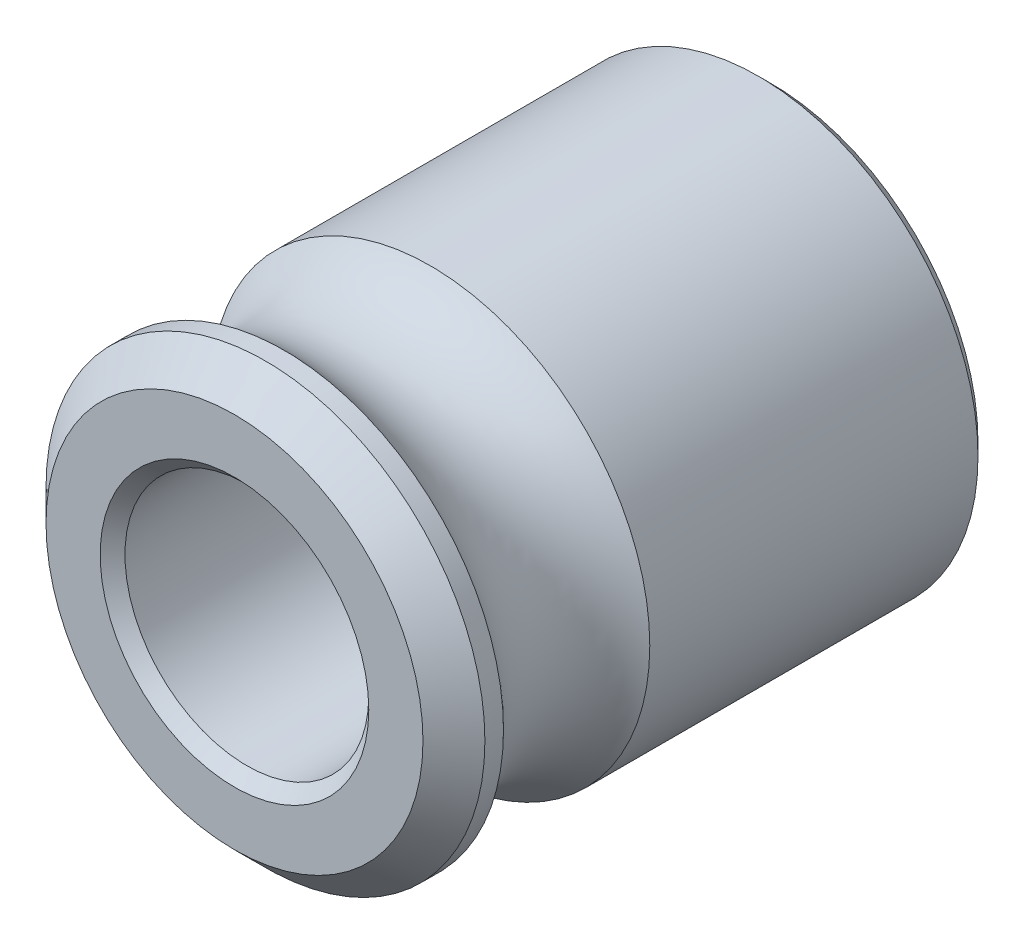
SolidWorks part; units mm, degrees
material "Chrome Stainless Steel"
ref_plane "Front Plane" through (0, 0, 0) normal (0, 0, 1) x (1, 0, 0)
ref_plane "Top Plane" through (0, 0, 0) normal (0, 1, 0) x (1, 0, 0)
ref_plane "Right Plane" through (0, 0, 0) normal (1, 0, 0) x (0, 0, -1)
sketch "Sketch1" plane through (0, 0, 0) normal (0, 0, 1) x (1, 0, 0)
  circle A0 centre (0, 0) radius 4.5
  circle A1 centre (0, 0) radius 2.5
  dimension "D1" = 9
  dimension "D2" = 5
extrude "Boss-Extrude1" add sketch "Sketch1" along normal blind 11
ref_axis "Axis1" through (0, 0, 11) along (0, 0, -1)
ref_plane "Plane1" through (0, 0, 0) normal (0, -1, 0) x (-1, 0, 0)
sketch "Sketch2" plane through (0, 0, 0) normal (0, -1, 0) x (-1, 0, 0)
  line L0 (0, -8.484) -> (3.8229, -8.484) construction
  line L1 (0, -11) -> (0, 0) construction
  line L2 (4.5, 0) -> (4.5, -11) construction
  line L3 (-4.5, -11) -> (4.5, -11) construction
  circle A0 centre (5.8229, -8.484) radius 2
  point P6 (3.8229, -8.484)
  point P11 (4.5, -9.984)
  point P12 (4.5, -6.984)
  dimension "D1" = 4
  dimension "D2" = 3
  dimension "D3" = 1.016
  dimension "D4" = 2.516
revolve "Cut-Revolve1" cut sketch "Sketch2" angle 360 about axis through (0, 0, 11) along (0, 0, -1)
chamfer "Chamfer1" distance 0.635 angle 45 1 edges at (4.5, 0, 11)
chamfer "Chamfer2" distance 0.254 angle 45 3 edges at (2.5, 0, 0) (4.5, 0, 0) (2.5, 0, 11)
